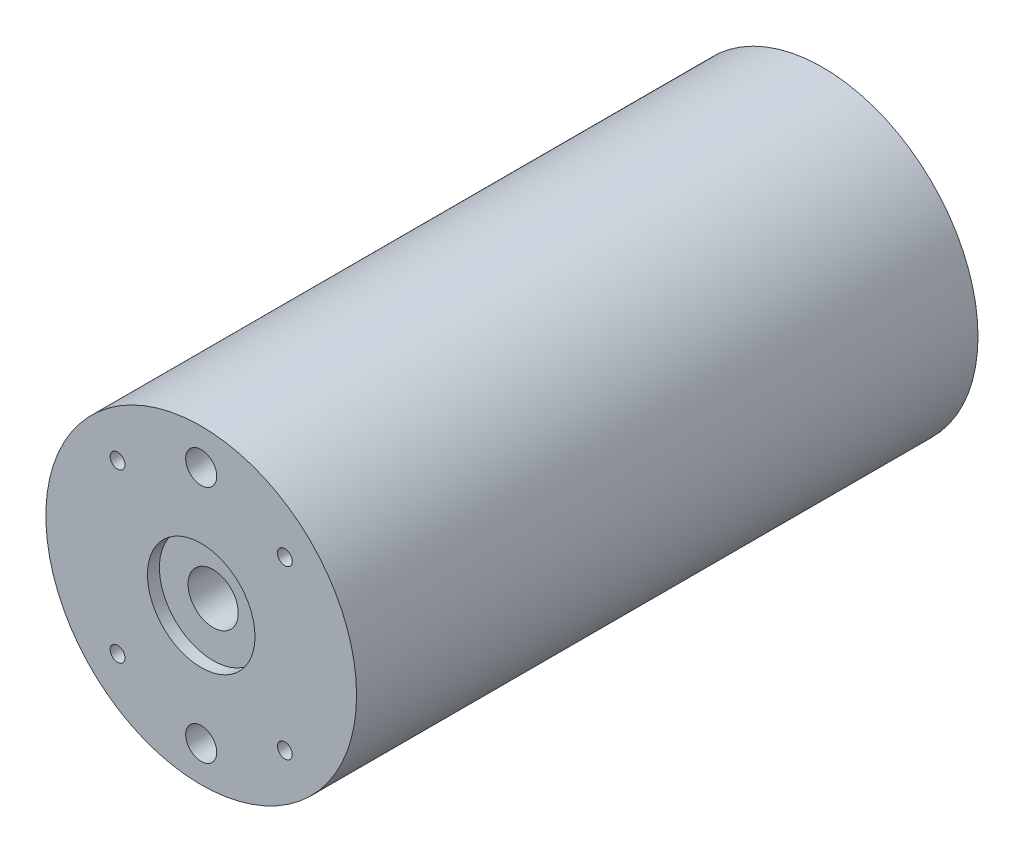
SolidWorks part; units mm, degrees
ref_plane "Front Plane" through (0, 0, 0) normal (0, 0, 1) x (1, 0, 0)
ref_plane "Top Plane" through (0, 0, 0) normal (0, 1, 0) x (1, 0, 0)
ref_plane "Right Plane" through (0, 0, 0) normal (1, 0, 0) x (0, 0, -1)
sketch "Sketch1" plane through (0, 0, 0) normal (0, 0, 1) x (1, 0, 0)
  circle A0 centre (0, 0) radius 41.275
  dimension "D1" = 82.55
extrude "Boss-Extrude1" add sketch "Sketch1" along normal blind 165.1
sketch "Sketch2" plane through (0, 0, 165.1) normal (0, 0, 1) x (1, 0, 0)
  circle A0 centre (0, 0) radius 14.2875
  dimension "D1" = 28.575
extrude "Cut-Extrude1" cut sketch "Sketch2" against normal blind 3.175
sketch "Sketch3" plane through (0, 0, 161.925) normal (0, 0, 1) x (1, 0, 0)
  circle A0 centre (0, 0) radius 6.6675
  dimension "D1" = 13.335
extrude "Cut-Extrude2" cut sketch "Sketch3" against normal blind 12.7
sketch "Sketch4" plane through (0, 0, 165.1) normal (0, 0, 1) x (1, 0, 0)
  circle A0 centre (0, 31.75) radius 4.1275
  circle A1 centre (0, -31.75) radius 4.1275
  dimension "D1" = 8.255
  dimension "D2" = 8.255
  dimension "D3" = 31.75
  dimension "D4" = 31.75
extrude "Cut-Extrude3" cut sketch "Sketch4" against normal blind 9.525
sketch "Sketch5" plane through (0, 0, 165.1) normal (0, 0, 1) x (1, 0, 0)
  line L1 (-22.225, -22.225) -> (22.225, -22.225) construction
  line L2 (-22.225, -22.225) -> (-22.225, 22.225) construction
  line L3 (-22.225, 22.225) -> (22.225, 22.225) construction
  line L4 (22.225, -22.225) -> (22.225, 22.225) construction
  line L5 (-22.225, -22.225) -> (22.225, 22.225) construction
  line L6 (-22.225, 22.225) -> (22.225, -22.225) construction
  circle A0 centre (-22.225, 22.225) radius 1.9685
  circle A1 centre (-22.225, -22.225) radius 1.9685
  circle A2 centre (22.225, -22.225) radius 1.9685
  circle A3 centre (22.225, 22.225) radius 1.9685
  point P0 (0, 0)
  dimension "D3" = 3.937
  dimension "D4" = 3.937
  dimension "D5" = 3.937
  dimension "D6" = 3.937
  dimension "D1" = 44.45
  dimension "D2" = 44.45
extrude "Cut-Extrude4" cut sketch "Sketch5" against normal blind 19.05
sketch "Sketch6" plane through (0, 0, 0) normal (0, 0, -1) x (-1, 0, 0)
  circle A0 centre (0, 0) radius 14.2875
  dimension "D1" = 28.575
extrude "Cut-Extrude5" cut sketch "Sketch6" against normal blind 3.175
